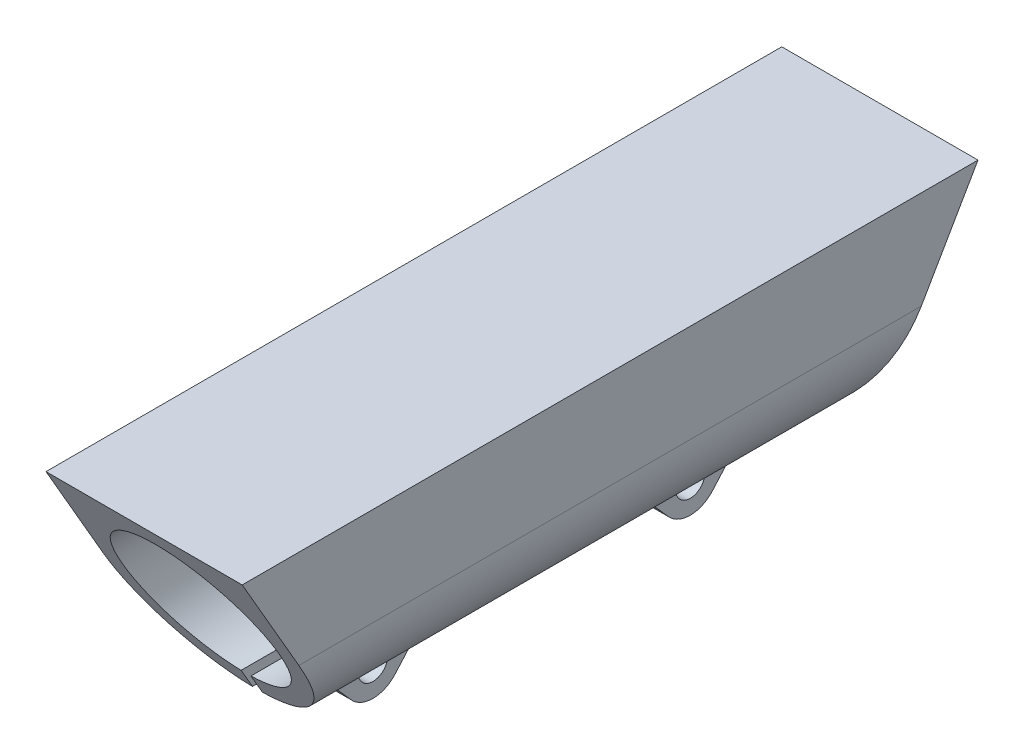
SolidWorks part; units mm, degrees
ref_plane "Alzado" through (0, 0, 0) normal (0, 0, 1) x (1, 0, 0)
ref_plane "Planta" through (0, 0, 0) normal (0, 1, 0) x (1, 0, 0)
ref_plane "Vista lateral" through (0, 0, 0) normal (1, 0, 0) x (0, 0, -1)
sketch "Croquis1" plane through (0, 0, 0) normal (0, 0, 1) x (1, 0, 0)
  line L0 (0, 0) -> (0, 17.9549) construction
  line L1 (-10, 10) -> (10, 10)
  line L2 (10, 10) -> (10, 0)
  line L3 (-10, 10) -> (-10, 0)
  line L4 (0.5, -7.9844) -> (0.5, -9.9875)
  line L5 (-0.5, -7.9844) -> (-0.5, -9.9875)
  arc A0 (0.5, -7.9844) -> (-0.5, -7.9844) centre (0, 0) ccw
  arc A1 (10, 0) -> (0.5, -9.9875) centre (0, 0) cw
  arc A2 (-10, 0) -> (-0.5, -9.9875) centre (0, 0) ccw
  point P0 (0, 0)
  point P10 (0, 0)
  point P11 (0, 0)
  point P15 (0, 10)
  dimension "D1" = 16
  dimension "D2" = 1
  dimension "D3" = 20
extrude "Saliente-Extruir1" add sketch "Croquis1" along normal blind 75
sketch "Croquis2" plane through (0, 0, 0) normal (1, 0, 0) x (0, 0, -1)
  line L0 (-60, -9.0579) -> (-55.9184, -13.6765)
  line L2 (-51.4224, -13.6765) -> (-47.3408, -9.0579)
  line L3 (-37.5, 10) -> (-37.5, -21.0758) construction
  line L4 (-75, 10) -> (0, 10) construction
  line L5 (-75, 0) -> (-75, -9.9875) construction
  line L6 (-60, -9.0579) -> (-47.3408, -9.0579)
  line L7 (-15, -9.0579) -> (-19.0816, -13.6765)
  line L8 (-23.5776, -13.6765) -> (-27.6592, -9.0579)
  line L9 (-15, -9.0579) -> (-27.6592, -9.0579)
  arc A0 (-55.9184, -13.6765) -> (-51.4224, -13.6765) centre (-53.6704, -11.6899) ccw
  circle A2 centre (-53.6704, -11.6899) radius 1.5
  circle A3 centre (-21.3296, -11.6899) radius 1.5
  arc A4 (-19.0816, -13.6765) -> (-23.5776, -13.6765) centre (-21.3296, -11.6899) cw
  point P2 (0, 0)
  point P3 (-60, -9.0579)
  point P12 (-55.7934, -13.9697)
  point P13 (-49.9288, -9.9875)
  point P14 (-52.4286, -16.0996)
  point P17 (-50.7675, -14.7278)
  point P24 (-47.3408, -9.9875)
  point P25 (0, 0)
  dimension "D2" = 1.5
  dimension "D3" = 3
  dimension "D1" = 15
extrude "Saliente-Extruir2" add sketch "Croquis2" along normal mid plane 4
sketch "Croquis5" plane through (0, 0, 0) normal (0, 0, 1) x (1, 0, 0)
  line L0 (-0.5, -7.9844) -> (-0.5, -14.6899)
  line L1 (-2, -14.6899) -> (2, -14.6899) construction
  line L2 (-0.5, -14.6899) -> (0.5, -14.6899)
  line L3 (0.5, -14.6899) -> (0.5, -7.9844)
  line L4 (-0.5, -7.9844) -> (0.5, -7.9844)
extrude "Cortar-Extruir1" cut sketch "Croquis5" against normal through all both and the other way through all
sketch "Croquis6" plane through (0, 0, 0) normal (1, 0, 0) x (0, 0, -1)
  line L0 (-75, 10) -> (-63.4557, -9.9875)
  line L1 (-75, -9.9875) -> (-59.1784, -9.9875) construction
  line L2 (-63.4557, -9.9875) -> (-75, -9.9875)
  line L3 (-75, -9.9875) -> (-75, 10)
  line L4 (-37.5, 10) -> (-37.5, -9.9875) construction
  line L5 (-75, 10) -> (0, 10) construction
  line L6 (-48.1623, -9.9875) -> (-26.8377, -9.9875) construction
  line L7 (-11.5443, -9.9875) -> (0, -9.9875)
  line L8 (0, -9.9875) -> (0, 10)
  line L9 (0, 10) -> (-11.5443, -9.9875)
  point P16 (-63.4557, -9.9875)
extrude "Cortar-Extruir2" cut sketch "Croquis6" against normal through all both and the other way through all
